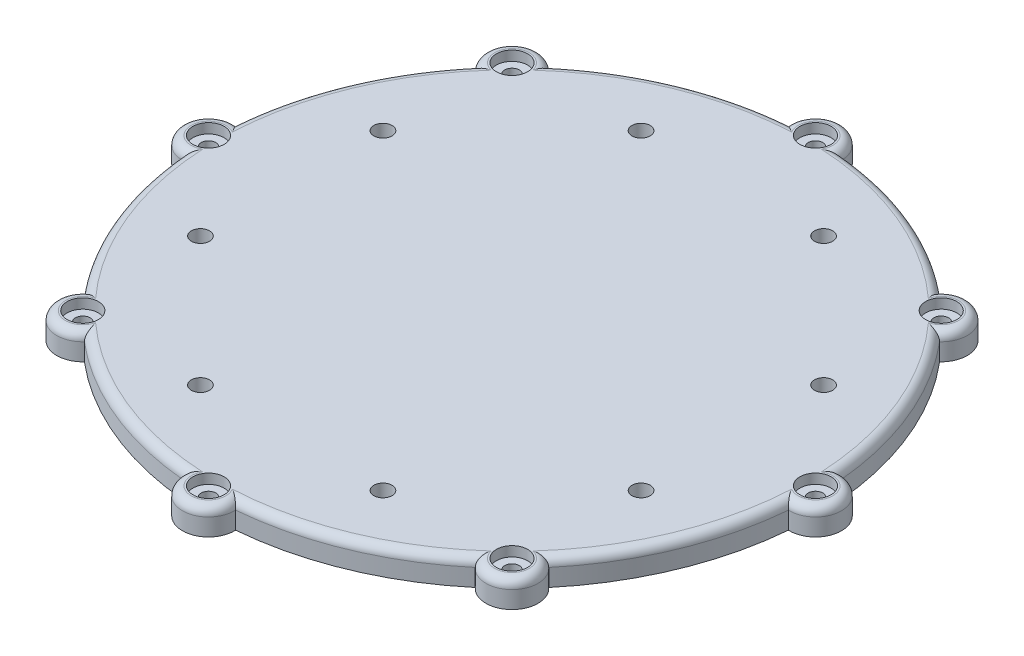
SolidWorks part; units mm, degrees
material "Alloy Steel"
ref_plane "Front Plane" through (0, 0, 0) normal (0, 0, 1) x (1, 0, 0)
ref_plane "Top Plane" through (0, 0, 0) normal (0, 1, 0) x (1, 0, 0)
ref_plane "Right Plane" through (0, 0, 0) normal (1, 0, 0) x (0, 0, -1)
sketch "Sketch1" plane through (0, 0, 0) normal (0, 1, 0) x (1, 0, 0)
  arc A0 (-133.886, 112.6923) -> (-174.3571, 14.9862) centre (0, 0) ccw
  arc A1 (14.9862, 174.3571) -> (-14.9862, 174.3571) centre (0, 175) ccw
  arc A2 (133.886, 112.6923) -> (112.6923, 133.886) centre (123.7437, 123.7437) ccw
  arc A3 (174.3571, -14.9862) -> (174.3571, 14.9862) centre (175, 0) ccw
  arc A4 (112.6923, -133.886) -> (133.886, -112.6923) centre (123.7437, -123.7437) ccw
  arc A5 (-14.9862, -174.3571) -> (14.9862, -174.3571) centre (0, -175) ccw
  arc A6 (-133.886, -112.6923) -> (-112.6923, -133.886) centre (-123.7437, -123.7437) ccw
  arc A7 (-174.3571, 14.9862) -> (-174.3571, -14.9862) centre (-175, 0) ccw
  arc A8 (-112.6923, 133.886) -> (-133.886, 112.6923) centre (-123.7437, 123.7437) ccw
  arc A9 (-174.3571, -14.9862) -> (-133.886, -112.6923) centre (0, 0) ccw
  arc A10 (-112.6923, -133.886) -> (-14.9862, -174.3571) centre (0, 0) ccw
  arc A11 (14.9862, -174.3571) -> (112.6923, -133.886) centre (0, 0) ccw
  arc A12 (133.886, -112.6923) -> (174.3571, -14.9862) centre (0, 0) ccw
  arc A13 (174.3571, 14.9862) -> (133.886, 112.6923) centre (0, 0) ccw
  arc A14 (112.6923, 133.886) -> (14.9862, 174.3571) centre (0, 0) ccw
  arc A15 (-14.9862, 174.3571) -> (-112.6923, 133.886) centre (0, 0) ccw
  point P22 (0, 0)
  dimension "D1" = 350
  dimension "D2" = 30
  dimension "D3" = 8
extrude "Boss-Extrude2" add sketch "Sketch1" along normal blind 15 contours A0 A7 A9 A6 A10 A5 A11 A4 A12 A3 A13 A2 A14 A1 A15 A8
sketch "Sketch2" plane through (0, 15, 0) normal (0, 1, 0) x (1, 0, 0)
  line L0 (0, 0) -> (0, 175) construction
  circle A0 centre (0, 0) radius 175
hole_wizard "CBORE for M8 Hex Head Bolt1" positions "Sketch3" profile "Sketch5" counterbore size "M8" standard "ANSI Metric" end condition through all
sketch "Sketch3" plane through (0, 15, 0) normal (0, 1, 0) x (1, 0, 0)
  point P0 (0, 175)
sketch "Sketch5" plane through (0, 15, -175) normal (1, 0, 0) x (0, 0, 1)
  line L0 (0, 0) -> (0, 15)
  line L1 (0, 15) -> (4.2, 15)
  line L3 (4.2, 15) -> (4.2, 5.68)
  line L4 (4.2, 5.68) -> (9.005, 5.68)
  line L5 (9.005, 5.68) -> (9.005, 0)
  line L7 (9.005, 0) -> (0, 0)
  line L11 (0, -6.35) -> (0, 107.95) construction
  dimension "Thru Hole Dia." = 8.4
  dimension "Thru Hole Depth" = 15
  dimension "C'Bore Dia." = 18.01
  dimension "C'Bore Depth" = 5.68
pattern_circular "CirPattern1" count 8 over 360 about axis through (0, 0, 0) along (0, 1, 0) of "CBORE for M8 Hex Head Bolt1"
sketch "Sketch6" plane through (0, 0, 0) normal (0, -1, 0) x (1, 0, 0)
  line L0 (0, 0) -> (0, -137.5) construction
  line L1 (0, 0) -> (-52.619, -127.0334) construction
  circle A0 centre (0, 0) radius 137.5
  dimension "D1" = 275
  dimension "D2" = 22.5
hole_wizard "CSK for M10 Flat Head Machine Screw1" positions "3DSketch2" profile "Sketch8" countersink size "M10" standard "ANSI Metric" end condition through all
sketch3d "3DSketch2"
  point P0 (-52.619, 0, -127.0334)
sketch "Sketch8" plane through (-52.619, 0, -127.0334) normal (1, 0, 0) x (0, 0, -1)
  line L0 (0, 0) -> (0, 15)
  line L1 (0, 15) -> (5.25, 15)
  line L2 (5.25, 15) -> (5.25, 4.75)
  line L3 (5.25, 4.75) -> (10, 0)
  line L5 (10, 0) -> (0, 0)
  line L6 (-5.25, 4.75) -> (-10, 0) construction
  line L11 (0, -6.35) -> (0, 107.95) construction
  dimension "Thru Hole Dia." = 10.5
  dimension "Thru Hole Depth" = 15
  dimension "Near C'Sink Dia." = 20
  dimension "Near C'Sink Angle" = 90
pattern_circular "CirPattern2" count 8 over 360 about axis through (0, 0, 0) along (0, 1, 0) of "CSK for M10 Flat Head Machine Screw1"
fillet "Fillet1" radius 5 16 edges at (-190, 15, 0) (-134.3503, 15, -134.3503) (0, 15, -190) (134.3503, 15, -134.3503) (190, 15, 0) (134.3503, 15, 134.3503) (0, 15, 190) (-134.3503, 15, 134.3503) (-161.6789, 15, 66.9696) (-161.6789, 15, -66.9696) (-66.9696, 15, -161.6789) (66.9696, 15, -161.6789) (161.6789, 15, -66.9696) (161.6789, 15, 66.9696) (66.9696, 15, 161.6789) (-66.9696, 15, 161.6789)
